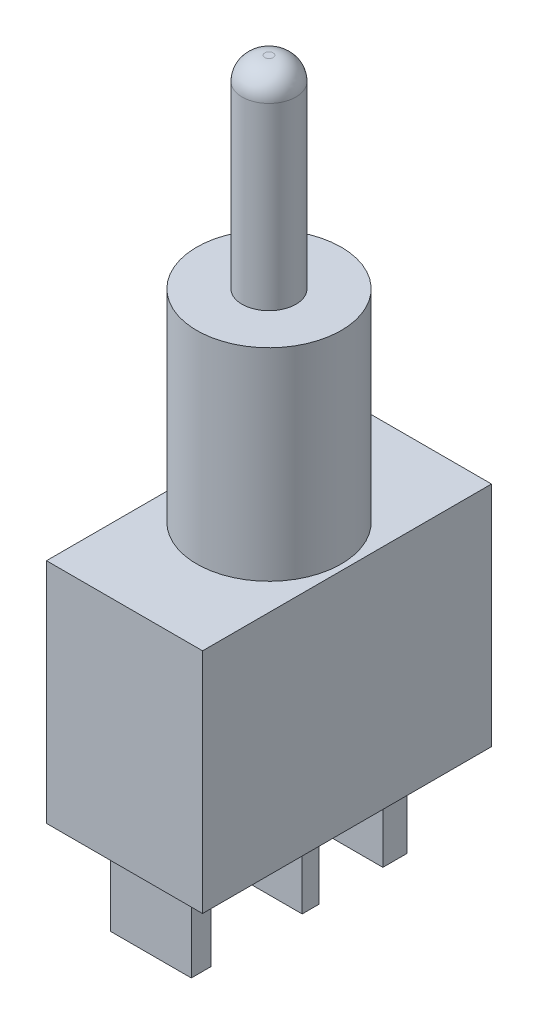
SolidWorks part; units mm, degrees
ref_plane "Front" through (0, 0, 0) normal (0, 0, 1) x (1, 0, 0)
ref_plane "Top" through (0, 0, 0) normal (0, 1, 0) x (1, 0, 0)
ref_plane "Right" through (0, 0, 0) normal (1, 0, 0) x (0, 0, -1)
sketch "Sketch1" plane through (0, 0, 0) normal (0, 1, 0) x (1, 0, 0)
  line L1 (0, 0) -> (6.86, 0)
  line L2 (0, 0) -> (0, 12.7)
  line L3 (0, 12.7) -> (6.86, 12.7)
  line L4 (6.86, 0) -> (6.86, 12.7)
  dimension "D1" = 12.7
  dimension "D2" = 6.86
extrude "Boss-Extrude1" add sketch "Sketch1" along normal blind 10
sketch "Sketch2" plane through (0, 0, 0) normal (0, -1, 0) x (1, 0, 0)
  line L1 (1.5184, -6.1716) -> (5.0663, -6.1716)
  line L2 (1.5184, -6.1716) -> (1.5184, -6.9056)
  line L3 (1.5184, -6.9056) -> (5.0663, -6.9056)
  line L4 (5.0663, -6.1716) -> (5.0663, -6.9056)
  line L5 (1.5184, -1.2984) -> (5.0663, -1.2984)
  line L6 (1.5184, -1.2984) -> (1.5184, -2.1751)
  line L7 (1.5184, -2.1751) -> (5.0663, -2.1751)
  line L8 (5.0663, -1.2984) -> (5.0663, -2.1751)
  line L9 (1.5184, -9.7195) -> (5.0663, -9.7195)
  line L10 (1.5184, -9.7195) -> (1.5184, -10.7696)
  line L11 (1.5184, -10.7696) -> (5.0663, -10.7696)
  line L12 (5.0663, -9.7195) -> (5.0663, -10.7696)
extrude "Boss-Extrude2" add sketch "Sketch2" along normal blind 4
sketch "Sketch3" plane through (0, 10, 0) normal (0, 1, 0) x (1, 0, 0)
  line L0 (3.43, 12.7) -> (3.43, 0) construction
  line L1 (6.86, 12.7) -> (0, 12.7) construction
  line L2 (0, 0) -> (6.86, 0) construction
  line L3 (0, 6.35) -> (6.86, 6.35) construction
  line L4 (0, 12.7) -> (0, 0) construction
  line L5 (6.86, 0) -> (6.86, 12.7) construction
  circle A0 centre (3.43, 6.35) radius 3.175
  dimension "D1" = 6.35
extrude "Boss-Extrude3" add sketch "Sketch3" along normal blind 8.89
sketch "Sketch4" plane through (0, 18.89, 0) normal (0, 1, 0) x (1, 0, 0)
  circle A0 centre (3.43, 6.35) radius 1.1823
extrude "Boss-Extrude4" add sketch "Sketch4" along normal blind 8.89
fillet "Fillet1" radius 1 1 edges at (3.43, 27.78, -5.1677)
